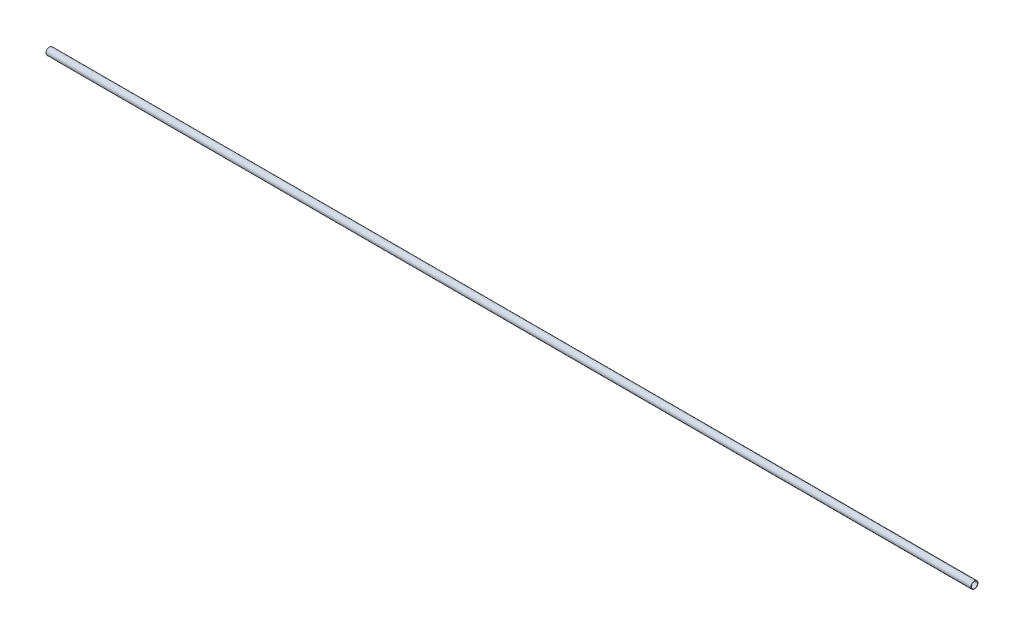
SolidWorks part; units mm, degrees
material "Galvanized Steel"
ref_plane "Front Plane" through (0, 0, 0) normal (0, 0, 1) x (1, 0, 0)
ref_plane "Top Plane" through (0, 0, 0) normal (0, 1, 0) x (1, 0, 0)
ref_plane "Right Plane" through (0, 0, 0) normal (1, 0, 0) x (0, 0, -1)
sketch "Sketch3" plane through (0, 0, 0) normal (1, 0, 0) x (0, 0, -1)
  circle A0 centre (0, 0) radius 10.4648
  circle A1 centre (0, 0) radius 11.7094
  dimension "D1" = 20.9296
  dimension "D2" = 23.4188
extrude "Boss-Extrude1" add sketch "Sketch3" along normal blind 3048
